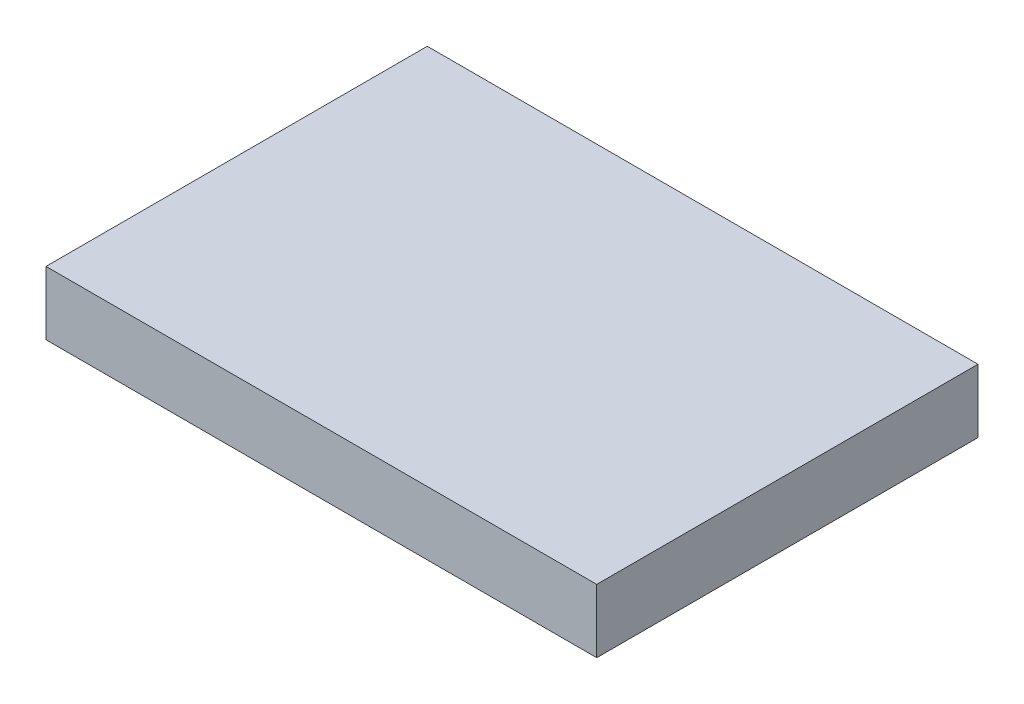
SolidWorks part; units mm, degrees
ref_plane "前视基准面" through (0, 0, 0) normal (0, 0, 1) x (1, 0, 0)
ref_plane "上视基准面" through (0, 0, 0) normal (0, 1, 0) x (1, 0, 0)
ref_plane "右视基准面" through (0, 0, 0) normal (1, 0, 0) x (0, 0, -1)
other "Configuration Table"
sketch "草图1" plane through (0, 0, 0) normal (0, 0, 1) x (1, 0, 0)
  line L1 (-130, -15) -> (130, -15)
  line L2 (-130, -15) -> (-130, 15)
  line L3 (-130, 15) -> (130, 15)
  line L4 (130, -15) -> (130, 15)
  line L5 (-130, -15) -> (130, 15) construction
  line L6 (-130, 15) -> (130, -15) construction
  point P0 (0, 0)
extrude "凸台-拉伸1" add sketch "草图1" along normal blind 180
